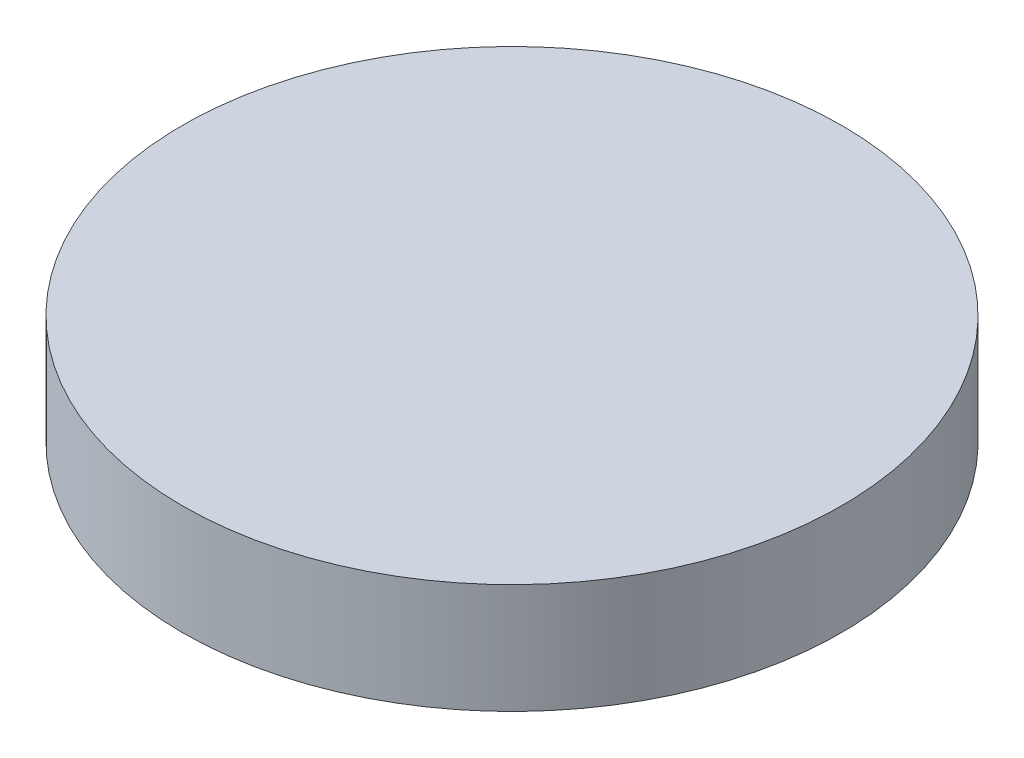
SolidWorks part; units mm, degrees
ref_plane "Front Plane" through (0, 0, 0) normal (0, 0, 1) x (1, 0, 0)
ref_plane "Top Plane" through (0, 0, 0) normal (0, 1, 0) x (1, 0, 0)
ref_plane "Right Plane" through (0, 0, 0) normal (1, 0, 0) x (0, 0, -1)
sketch "Sketch1" plane through (0, 0, 0) normal (0, 1, 0) x (1, 0, 0)
  circle A0 centre (0, 0) radius 76.2
  dimension "D1" = 152.4
extrude "Boss-Extrude1" add sketch "Sketch1" against normal blind 25.4
sketch "Sketch2" plane through (0, 0, 0) normal (0, 1, 0) x (1, 0, 0)
  line L1 (-50.8, -38.1) -> (50.8, -38.1)
  line L2 (-50.8, -38.1) -> (-50.8, 38.1)
  line L3 (-50.8, 38.1) -> (50.8, 38.1)
  line L4 (50.8, -38.1) -> (50.8, 38.1)
  line L5 (-50.8, -38.1) -> (50.8, 38.1) construction
  line L6 (-50.8, 38.1) -> (50.8, -38.1) construction
  point P0 (0, 0)
  dimension "D1" = 76.2
  dimension "D2" = 101.6
